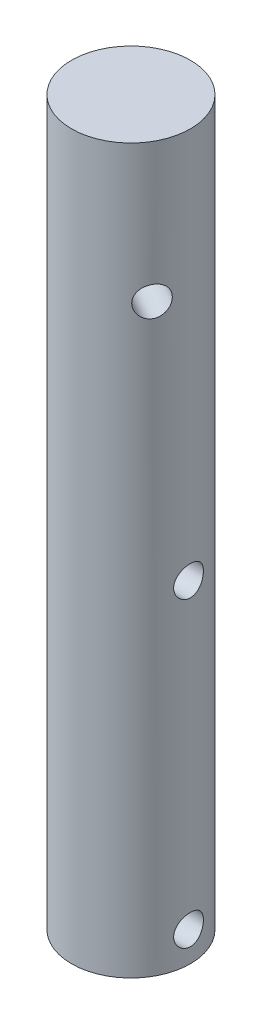
SolidWorks part; units mm, degrees
other "Passive Wheel Axle"
other "Passive Wheel Axle Left"
ref_plane "Front Plane" through (0, 0, 0) normal (0, 0, 1) x (1, 0, 0)
ref_plane "Top Plane" through (0, 0, 0) normal (0, 1, 0) x (1, 0, 0)
ref_plane "Right Plane" through (0, 0, 0) normal (1, 0, 0) x (0, 0, -1)
sketch3d "Twelve millimetre axle stock sketch datum points"
  point P0 (-19.0092, -283, -53.2449)
  point P1 (-9.0092, -283, -53.2449)
  point P2 (-19.0092, -283, -63.2449)
ref_plane "Twelve millimetre axle stock sketch plane" through (0, -283, 0) normal (0, 1, 0) x (1, 0, 0)
sketch "Twelve millimetre axle stock sketch" plane through (0, -283, 0) normal (0, 1, 0) x (1, 0, 0)
  circle A0 centre (-19.0092, 53.2449) radius 6
extrude "Twelve millimetre axle stock" add sketch "Twelve millimetre axle stock sketch" along normal blind 73 separate body
sketch3d "Front collar pin sketch datum points"
  point P0 (-26.0092, -213, -53.2449)
  point P1 (-26.0092, -203, -53.2449)
  point P2 (-26.0092, -213, -43.2449)
ref_plane "Front collar pin sketch plane" through (-26.0092, 0, 0) normal (1, 0, 0) x (0, 0, -1)
sketch "Front collar pin sketch" plane through (-26.0092, 0, 0) normal (1, 0, 0) x (0, 0, -1)
  circle A0 centre (53.2449, -213) radius 1.5
extrude "Front collar pin" cut sketch "Front collar pin sketch" along normal blind 14
sketch3d "Rear collar pin sketch datum points"
  point P0 (-26.0092, -243.5, -53.2449)
  point P1 (-26.0092, -233.5, -53.2449)
  point P2 (-26.0092, -243.5, -43.2449)
ref_plane "Rear collar pin sketch plane" through (-26.0092, 0, 0) normal (1, 0, 0) x (0, 0, -1)
sketch "Rear collar pin sketch" plane through (-26.0092, 0, 0) normal (1, 0, 0) x (0, 0, -1)
  circle A0 centre (53.2449, -243.5) radius 1.5
extrude "Rear collar pin" cut sketch "Rear collar pin sketch" along normal blind 14
sketch3d "Hub drive pin sketch datum points"
  point P0 (-25.0714, -269, -56.7449)
  point P1 (-20.0714, -269, -65.4051)
  point P2 (-25.0714, -259, -56.7449)
ref_plane "Hub drive pin sketch plane" through (-43.3748, 0, -25.0424) normal (0.866, 0, 0.5) x (0.5, 0, -0.866)
sketch "Hub drive pin sketch" plane through (-43.3748, 0, -25.0424) normal (0.866, 0, 0.5) x (0.5, 0, -0.866)
  circle A0 centre (36.6068, -269) radius 1.5
extrude "Hub drive pin" cut sketch "Hub drive pin sketch" along normal blind 14
sketch3d "Mirror1 profile datum points"
  point P0 (0, 0, 0)
  point P1 (10, 0, 0)
  point P2 (0, 0, 10)
ref_plane "Mirror1 profile plane" through (0, 0, 0) normal (0, -1, 0) x (-1, 0, 0)
mirror "Mirror1" about plane through (0, 0, 0) normal (0, -1, 0) of bodies 104
delete or keep bodies "Remove1" type delete bodies bodies 104
